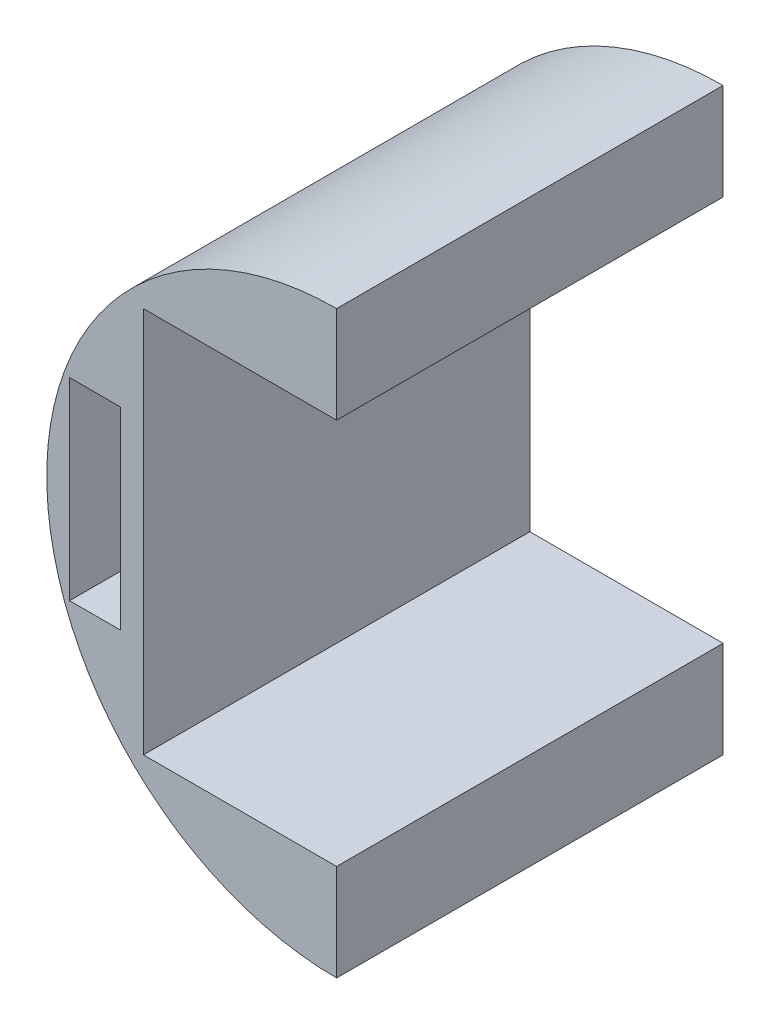
SolidWorks part; units mm, degrees
ref_plane "Front Plane" through (0, 0, 0) normal (1, 0, 0) x (0, 1, 0)
ref_plane "Top Plane" through (0, 0, 0) normal (0, 0, 1) x (0, 1, 0)
ref_plane "Right Plane" through (0, 0, 0) normal (0, 1, 0) x (-1, 0, 0)
sketch "Sketch1" plane through (0, 0, 0) normal (0, 0, 1) x (0, 1, 0)
  line L0 (0, 0) -> (5, 0)
  line L1 (30, 0) -> (25, 0)
  line L2 (5, 0) -> (5, 10)
  line L3 (25, 0) -> (25, 10)
  line L4 (5, 10) -> (25, 10)
  arc A0 (0, 0) -> (30, 0) centre (15, 0) cw
  dimension "D1" = 15
  dimension "D2" = 5
  dimension "D3" = 5
  dimension "D4" = 10
  dimension "10" = 10
extrude "Boss-Extrude1" add sketch "Sketch1" along normal blind 20 contours A0 L1 L3 L4 L2 L0
sketch "Sketch2" plane through (0, 0, 20) normal (0, 0, 1) x (1, 0, 0)
  line L0 (-10, 25) -> (-11.1803, 25)
  line L1 (-10, 5) -> (-11.1803, 5)
  line L12 (-13.8197, 10) -> (-11.1803, 10)
  line L13 (-13.8197, 10) -> (-13.8197, 20)
  line L14 (-13.8197, 20) -> (-11.1803, 20)
  line L15 (-11.1803, 10) -> (-11.1803, 20)
  arc A0 (0, 30) -> (0, 0) centre (0, 15) ccw construction
extrude "Cut-Extrude1" cut sketch "Sketch2" against normal blind 20 contours L13 L14 L15 L12
